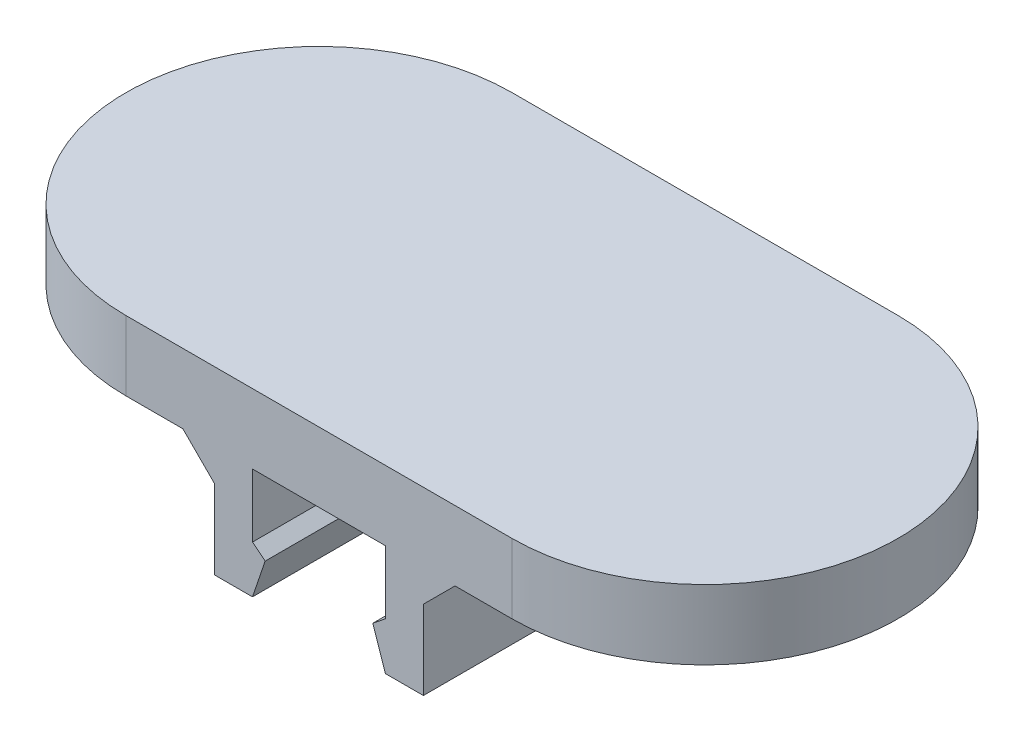
SolidWorks part; units mm, degrees
ref_plane "Plan de face" through (0, 0, 0) normal (0, 0, 1) x (1, 0, 0)
ref_plane "Plan de dessus" through (0, 0, 0) normal (0, 1, 0) x (1, 0, 0)
ref_plane "Plan de droite" through (0, 0, 0) normal (1, 0, 0) x (0, 0, -1)
sketch "Esquisse1" plane through (0, 0, 0) normal (0, 1, 0) x (1, 0, 0)
  line L0 (-6.1, 0) -> (6.1, 0) construction
  line L1 (-6.1, 6.1) -> (6.1, 6.1)
  line L2 (-6.1, -6.1) -> (6.1, -6.1)
  arc A0 (-6.1, 6.1) -> (-6.1, -6.1) centre (-6.1, 0) ccw
  arc A1 (6.1, -6.1) -> (6.1, 6.1) centre (6.1, 0) ccw
  point P2 (0, 0)
  dimension "D2" = 12.2
  dimension "D1" = 12.2
extrude "Boss.-Extru.1" add sketch "Esquisse1" along normal blind 2.2
sketch "Esquisse2" plane through (0, 0, 0) normal (0, 0, 1) x (1, 0, 0)
  line L0 (-2.1, 0) -> (-2.1, -2)
  line L1 (-2.1, -2) -> (-1.7, -2.3209)
  line L2 (-1.7, -2.3209) -> (-2.1, -3.5)
  line L3 (-2.1, -3.5) -> (-3.3, -3.5)
  line L4 (-3.3, -3.5) -> (-3.3, 0)
  line L5 (-3.3, 0) -> (-2.1, 0)
  line L6 (-12.2, 0) -> (-6.1, 0) construction
  line L14 (0, -55) -> (0, 55) construction
  line L15 (2.1, -3.5) -> (3.3, -3.5)
  line L16 (1.7, -2.3209) -> (2.1, -3.5)
  line L17 (2.1, -2) -> (1.7, -2.3209)
  line L18 (2.1, 0) -> (2.1, -2)
  line L19 (3.3, 0) -> (2.1, 0)
  line L20 (3.3, -3.5) -> (3.3, 0)
  dimension "D1" = 2.1
  dimension "D2" = 0.4
  dimension "D3" = 1.2
  dimension "D4" = 1.5
  dimension "D5" = 110
  dimension "D6" = 3.5
extrude "Boss.-Extru.2" add sketch "Esquisse2" along normal mid plane 12.2
chamfer "Chanfrein1" distance 1 angle 45 2 edges at (-3.3, 0, 0) (3.3, 0, 0)
